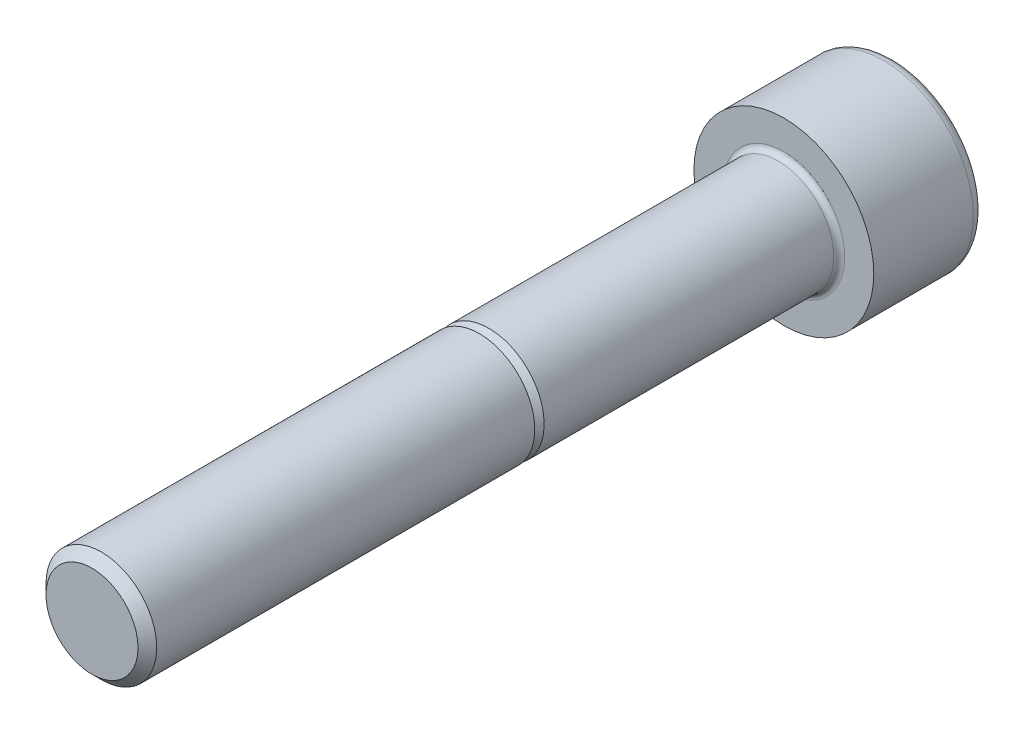
SolidWorks part; units mm, degrees
material "6061-O (SS)"
ref_plane "Ebene vorne" through (0, 0, 0) normal (0, 0, 1) x (1, 0, 0)
ref_plane "Ebene oben" through (0, 0, 0) normal (0, 1, 0) x (1, 0, 0)
ref_plane "Ebene rechts" through (0, 0, 0) normal (1, 0, 0) x (0, 0, -1)
ref_plane "Ebene1" through (0, 0, 0) normal (0, -1, 0) x (1, 0, 0)
sketch "Skizze1" plane through (0, 0, 0) normal (0, -1, 0) x (1, 0, 0)
  line L0 (4, 50) -> (0, 50)
  line L1 (0, 50) -> (0, -8)
  line L2 (0, -8) -> (6.5, -8)
  line L3 (6.5, -8) -> (6.5, 0)
  line L4 (6.5, 0) -> (4, 0)
  line L5 (4, 0) -> (4, 21.3234)
  line L6 (4, 21.3234) -> (3.3234, 22)
  line L7 (3.3234, 22) -> (4, 22)
  line L8 (4, 22) -> (4, 50)
  line L9 (0, 50) -> (0, -8) construction
revolve "Rotation1" add sketch "Skizze1" angle 360 about L9
sketch "Skizze2" plane through (0, 0, -8) normal (0, 0, -1) x (-1, 0, 0)
  line L0 (3, -1.7321) -> (3, 1.7321)
  line L1 (3, 1.7321) -> (0, 3.4641)
  line L2 (0, 3.4641) -> (-3, 1.7321)
  line L3 (-3, 1.7321) -> (-3, -1.7321)
  line L4 (-3, -1.7321) -> (0, -3.4641)
  line L5 (0, -3.4641) -> (3, -1.7321)
extrude "Schnitt-Linear austragen1" cut sketch "Skizze2" against normal blind 4
sketch "Skizze3" plane through (0, 0, 0) normal (0, 1, 0) x (1, 0, 0)
  line L0 (3, 4) -> (0, 4)
  line L1 (0, 4) -> (0, 2.2679)
  line L2 (0, 2.2679) -> (3, 4)
  line L3 (0, 4) -> (0, 2.2679) construction
revolve "Schnitt-Rotation1" cut sketch "Skizze3" angle 360 about L3
chamfer "Fase1" distance 0.6766 angle 45 1 edges at (-4, 0, 50)
fillet "Verrundung1" radius 0.4 1 edges at (-4, 0, 0)
fillet "Verrundung2" radius 0.8 1 edges at (-6.5, 0, -8)
